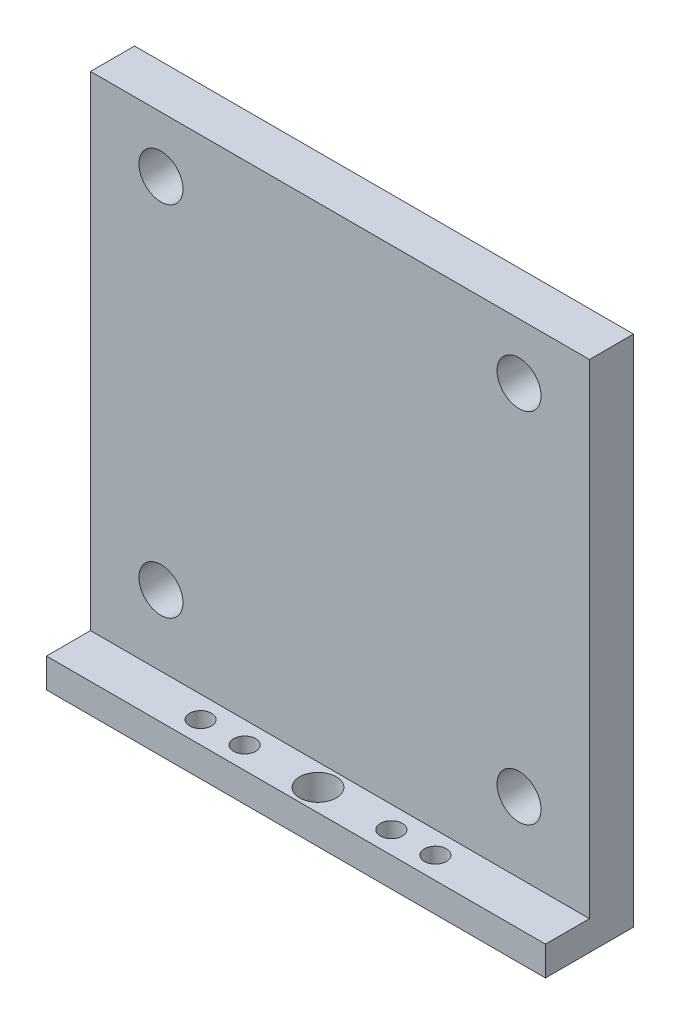
SolidWorks part; units mm, degrees
material "1060 Alloy"
ref_plane "Front Plane" through (0, 0, 0) normal (0, 0, 1) x (1, 0, 0)
ref_plane "Top Plane" through (0, 0, 0) normal (0, 1, 0) x (1, 0, 0)
ref_plane "Right Plane" through (0, 0, 0) normal (1, 0, 0) x (0, 0, -1)
sketch "Sketch1" plane through (0, 0, 0) normal (1, 0, 0) x (0, 0, -1)
  line L0 (0, 0) -> (6, 0)
  line L1 (6, 0) -> (6, 35)
  line L2 (6, 35) -> (3, 35)
  line L3 (3, 35) -> (3, 2)
  line L4 (3, 2) -> (0, 2)
  line L5 (0, 2) -> (0, 0)
  line L7 (-16.05, 5) -> (3, 5) construction
  line L8 (-16.05, 5) -> (-16.05, 35) construction
  line L9 (-16.05, 35) -> (3, 35) construction
  line L10 (3, 5) -> (3, 35) construction
  dimension "D1" = 2
  dimension "D2" = 3
  dimension "D3" = 3
  dimension "D4" = 30
  dimension "D5" = 19.05
  dimension "D6" = 3
extrude "Boss-Extrude1" add sketch "Sketch1" along normal blind 34
sketch "Sketch2" plane through (0, 0, -3) normal (0, 0, 1) x (1, 0, 0)
  line L0 (17, 19) -> (17, 2) construction
  line L1 (4.8, 6.8) -> (29.2, 6.8) construction
  line L2 (4.8, 6.8) -> (4.8, 31.2) construction
  line L3 (4.8, 31.2) -> (29.2, 31.2) construction
  line L4 (29.2, 6.8) -> (29.2, 31.2) construction
  line L5 (4.8, 6.8) -> (29.2, 31.2) construction
  line L6 (4.8, 31.2) -> (29.2, 6.8) construction
  line L7 (34, 2) -> (0, 2) construction
  line L9 (2, 4) -> (32, 4) construction
  line L10 (2, 4) -> (2, 34) construction
  line L11 (2, 34) -> (32, 34) construction
  line L12 (32, 4) -> (32, 34) construction
  line L13 (2, 4) -> (32, 34) construction
  line L14 (2, 34) -> (32, 4) construction
  circle A0 centre (29.2, 31.2) radius 1.5
  circle A1 centre (4.8, 31.2) radius 1.5
  circle A2 centre (4.8, 6.8) radius 1.5
  circle A3 centre (29.2, 6.8) radius 1.5
  point P0 (17, 19)
  dimension "D4" = 3
  dimension "D1" = 24.4
  dimension "D2" = 30
  dimension "D3" = 2
extrude "Cut-Extrude1" cut sketch "Sketch2" against normal through all
sketch "Sketch3" plane through (0, 2, 0) normal (0, 1, 0) x (1, 0, 0)
  line L0 (9, 1.5) -> (12, 1.5) construction
  line L1 (12, 1.5) -> (17, 1.5) construction
  line L2 (17, 1.5) -> (22, 1.5) construction
  line L3 (22, 1.5) -> (25, 1.5) construction
  line L4 (17, 1.5) -> (17, 0) construction
  line L6 (25, 1.5) -> (34, 1.5) construction
  line L7 (34, 3) -> (34, 0) construction
  line L8 (34, 0) -> (0, 0) construction
  circle A0 centre (17, 1.5) radius 1.25
  circle A1 centre (22, 1.5) radius 0.75
  circle A2 centre (25, 1.5) radius 0.75
  circle A3 centre (12, 1.5) radius 0.75
  circle A4 centre (9, 1.5) radius 0.75
  point P12 (0, 0)
  point P16 (25.8517, 1.5)
  point P17 (16.9162, 1.5)
  dimension "D1" = 2.5
  dimension "D2" = 1.5
  dimension "D3" = 5
  dimension "D4" = 3
extrude "Cut-Extrude2" cut sketch "Sketch3" against normal through all
